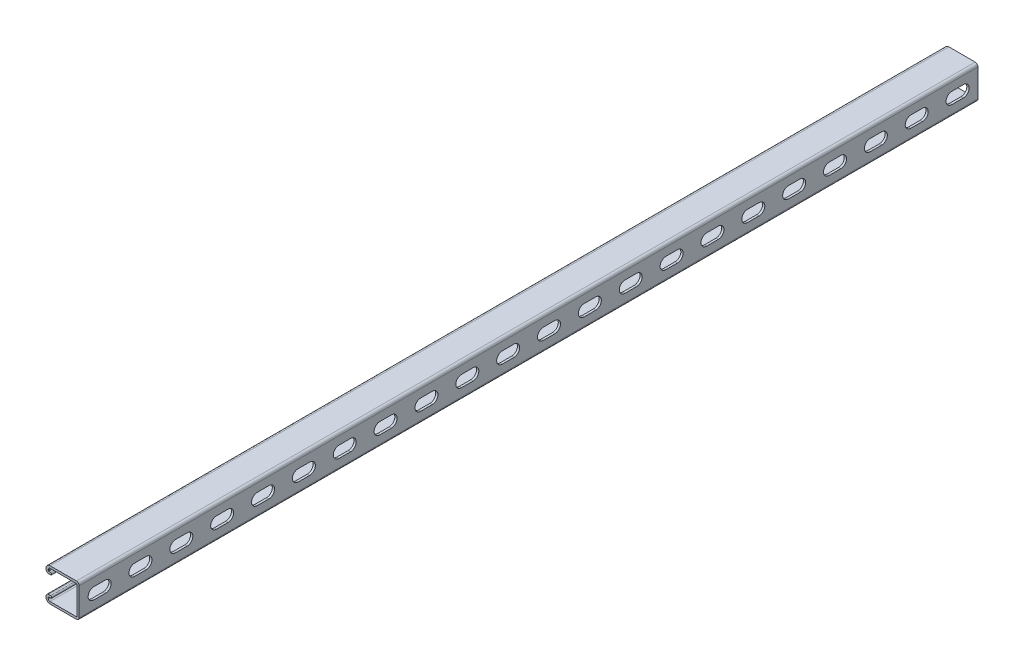
SolidWorks part; units mm, degrees
material "Galvanized Steel"
ref_plane "Front Plane" through (0, 0, 0) normal (0, 0, 1) x (1, 0, 0)
ref_plane "Top Plane" through (0, 0, 0) normal (0, 1, 0) x (1, 0, 0)
ref_plane "Right Plane" through (0, 0, 0) normal (1, 0, 0) x (0, 0, -1)
sketch "Sketch1" plane through (0, 0, 0) normal (0, 0, 1) x (1, 0, 0)
  line L0 (0, 0) -> (-41.275, 0) construction
  line L3 (-41.275, 20.6375) -> (0, 20.6375) construction
  line L4 (-41.275, 20.6375) -> (-41.275, -20.6375) construction
  line L5 (-41.275, -20.6375) -> (0, -20.6375) construction
  line L6 (0, 20.6375) -> (0, -20.6375) construction
  line L7 (-36.2267, 20.6375) -> (-3.4607, 20.6375)
  line L8 (0, 17.1767) -> (0, -17.1767)
  line L9 (-2.794, -17.1767) -> (-2.794, 17.1767)
  line L10 (-3.4608, 17.8435) -> (-36.2267, 17.8435)
  line L11 (-41.275, 15.5892) -> (-41.275, 14.5732)
  line L12 (-37.8142, 11.1125) -> (-35.5346, 11.1125)
  line L14 (-35.5346, 13.9065) -> (-37.8142, 13.9065)
  line L15 (-38.481, 14.5732) -> (-38.481, 15.5892)
  line L16 (-38.481, -14.5733) -> (-38.481, -15.5893)
  line L17 (-35.5346, -13.9065) -> (-37.8142, -13.9065)
  line L18 (-37.8142, -11.1125) -> (-35.5346, -11.1125)
  line L19 (-41.275, -15.5893) -> (-41.275, -14.5733)
  line L20 (-3.4607, -17.8435) -> (-36.2267, -17.8435)
  line L21 (-36.2267, -20.6375) -> (-3.4607, -20.6375)
  line L22 (-2.794, -20.6375) -> (-2.794, 20.6375) construction
  arc A1 (0, 17.1767) -> (-3.4607, 20.6375) centre (-3.4607, 17.1767) ccw
  arc A2 (-2.794, 17.1767) -> (-3.4608, 17.8435) centre (-3.4607, 17.1767) ccw
  arc A4 (-36.2267, 20.6375) -> (-41.275, 15.5892) centre (-36.2267, 15.5892) ccw
  arc A5 (-41.275, 14.5732) -> (-37.8142, 11.1125) centre (-37.8142, 14.5732) ccw
  arc A6 (-35.5346, 11.1125) -> (-35.5346, 13.9065) centre (-35.5346, 12.5095) ccw
  arc A7 (-37.8142, 13.9065) -> (-38.481, 14.5732) centre (-37.8142, 14.5732) cw
  arc A8 (-38.481, 15.5892) -> (-36.2267, 17.8435) centre (-36.2267, 15.5892) cw
  arc A9 (-38.481, -15.5893) -> (-36.2267, -17.8435) centre (-36.2267, -15.5893) ccw
  arc A10 (-37.8142, -13.9065) -> (-38.481, -14.5733) centre (-37.8142, -14.5733) ccw
  arc A11 (-35.5346, -11.1125) -> (-35.5346, -13.9065) centre (-35.5346, -12.5095) cw
  arc A12 (-41.275, -14.5733) -> (-37.8142, -11.1125) centre (-37.8142, -14.5733) cw
  arc A13 (-36.2267, -20.6375) -> (-41.275, -15.5893) centre (-36.2267, -15.5893) cw
  arc A14 (-2.794, -17.1767) -> (-3.4607, -17.8435) centre (-3.4607, -17.1767) cw
  arc A15 (0, -17.1767) -> (-3.4607, -20.6375) centre (-3.4607, -17.1767) cw
  point P24 (0, 20.6375)
  point P65 (-2.794, 0)
  dimension "D1" = 3.4608
  dimension "D2" = 5.0482
  dimension "D3" = 3.4608
  dimension "Ht." = 41.275
  dimension "Wd." = 41.275
  dimension "Thk." = 2.794
  dimension "D4" = 9.525
  dimension "D5" = 7.1374
extrude "Boss-Extrude1" add sketch "Sketch1" against normal blind 1117.6
sketch "Sketch3" plane through (0, 0, 0) normal (1, 0, 0) x (0, 0, -1)
  line L0 (0, 0) -> (1117.6, 0) construction
  point P2 (101.6, 0)
  point P3 (1016, 0)
  dimension "D1" = 101.6
  dimension "D2" = 101.6
  dimension "D3" = 1117.6
sketch "Sketch2" plane through (0, 0, 0) normal (1, 0, 0) x (0, 0, -1)
  line L0 (18.2562, 0) -> (32.5437, 0) construction
  line L1 (18.2562, 7.1437) -> (32.5437, 7.1437)
  line L2 (18.2562, -7.1437) -> (32.5437, -7.1437)
  line L3 (18.2562, 0) -> (0, 0) construction
  line L4 (25.4, 0) -> (76.2, 0) construction
  line L5 (0, -17.1767) -> (0, 17.1767) construction
  arc A0 (18.2562, 7.1437) -> (18.2562, -7.1437) centre (18.2562, 0) ccw
  arc A1 (32.5437, -7.1437) -> (32.5437, 7.1437) centre (32.5437, 0) ccw
  point P3 (25.4, 0)
  dimension "Hole to End" = 11.1125
  dimension "D2" = 25.4
extrude "Cut-Extrude1" cut sketch "Sketch2" against normal up to vertex (2.794 mm away) up to point (-2.794, 0, 0)
pattern_linear "LPattern1" count 22 spacing 50.8 along (0, 0, -1) of "Cut-Extrude1"
equation "\"D1@LPattern1\" = \"Slot Ctr.@Sketch2\""
equation "\"Hole Count@LPattern1\" = \"Lg.@Boss-Extrude1\" / \"D1@LPattern1\""
equation "\"D3@Sketch3\" = \"Lg.@Boss-Extrude1\""
